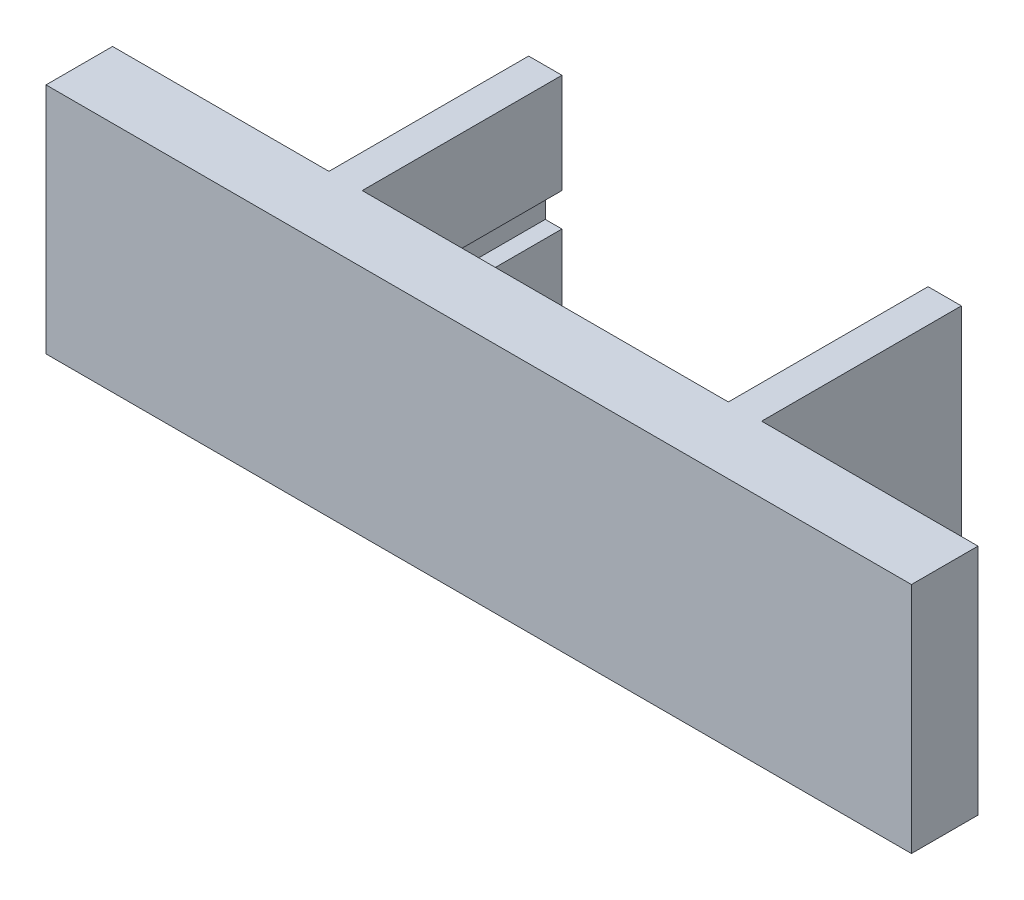
SolidWorks part; units mm, degrees
ref_plane "Front Plane" through (0, 0, 0) normal (0, 0, 1) x (1, 0, 0)
ref_plane "Top Plane" through (0, 0, 0) normal (0, 1, 0) x (1, 0, 0)
ref_plane "Right Plane" through (0, 0, 0) normal (1, 0, 0) x (0, 0, -1)
sketch "Sketch1" plane through (0, 0, 0) normal (0, 0, 1) x (1, 0, 0)
  line L1 (-41.275, -11.1125) -> (41.275, -11.1125)
  line L2 (-41.275, -11.1125) -> (-41.275, 11.1125)
  line L3 (-41.275, 11.1125) -> (41.275, 11.1125)
  line L4 (41.275, -11.1125) -> (41.275, 11.1125)
  line L5 (-41.275, -11.1125) -> (41.275, 11.1125) construction
  line L6 (-41.275, 11.1125) -> (41.275, -11.1125) construction
  point P0 (0, 0)
  dimension "D1" = 82.55
  dimension "D2" = 22.225
extrude "Boss-Extrude1" add sketch "Sketch1" along normal blind 6.35
sketch "Sketch3" plane through (0, 11.1125, 0) normal (0, 1, 0) x (1, 0, 0)
  line L0 (41.275, -6.35) -> (-41.275, -6.35) construction
  line L1 (-20.6375, -6.35) -> (-17.4625, -6.35)
  line L2 (-20.6375, -6.35) -> (-20.6375, 19.05)
  line L3 (-20.6375, 19.05) -> (-17.4625, 19.05)
  line L4 (-17.4625, -6.35) -> (-17.4625, 19.05)
  line L5 (0, 0) -> (0, 10.4514) construction
  line L6 (17.4625, -6.35) -> (17.4625, 19.05)
  line L7 (20.6375, 19.05) -> (17.4625, 19.05)
  line L8 (20.6375, -6.35) -> (20.6375, 19.05)
  line L9 (20.6375, -6.35) -> (17.4625, -6.35)
  dimension "D1" = 3.175
  dimension "D2" = 25.4
  dimension "D3" = 20.6375
extrude "Boss-Extrude2" add sketch "Sketch3" against normal up to surface (22.225 mm away) up to face at (0, -11.1125, 3.175)
sketch "Sketch2" plane through (0, 0, 0) normal (0, 0, 1) x (1, 0, 0)
  line L1 (-19.05, -1.5875) -> (19.05, -1.5875)
  line L2 (-19.05, -1.5875) -> (-19.05, 1.5875)
  line L3 (-19.05, 1.5875) -> (19.05, 1.5875)
  line L4 (19.05, -1.5875) -> (19.05, 1.5875)
  line L5 (-19.05, -1.5875) -> (19.05, 1.5875) construction
  line L6 (-19.05, 1.5875) -> (19.05, -1.5875) construction
  point P0 (0, 0)
  dimension "D1" = 3.175
  dimension "D2" = 38.1
extrude "Cut-Extrude3" cut sketch "Sketch2" against normal through all from offset 3.175
